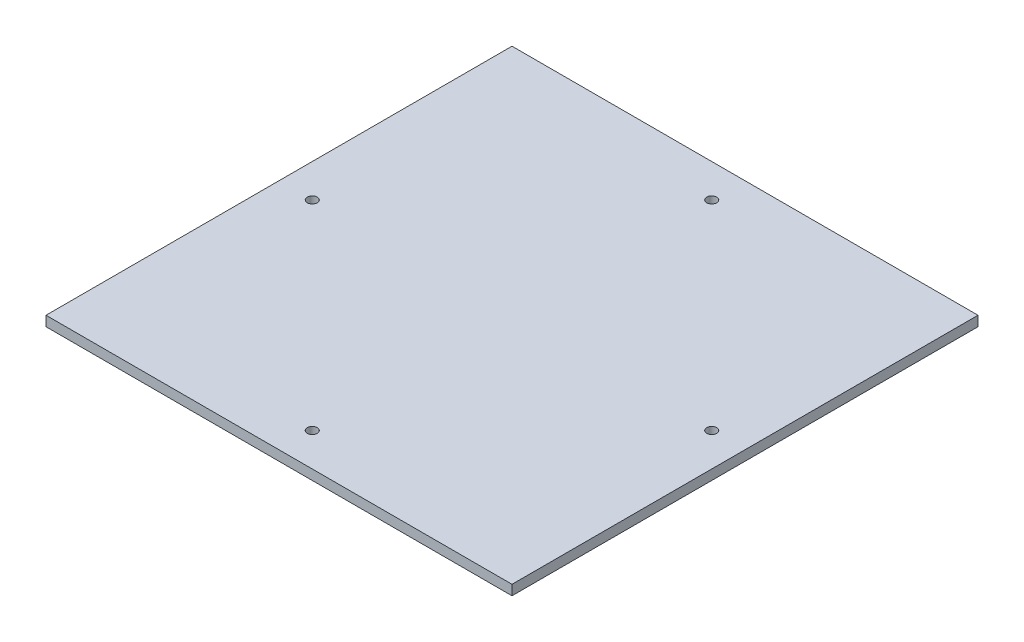
SolidWorks part; units mm, degrees
ref_plane "前视基准面" through (0, 0, 0) normal (0, 0, 1) x (1, 0, 0)
ref_plane "上视基准面" through (0, 0, 0) normal (0, 1, 0) x (1, 0, 0)
ref_plane "右视基准面" through (0, 0, 0) normal (1, 0, 0) x (0, 0, -1)
other "Configuration Table"
sketch "草图1" plane through (0, 0, 0) normal (0, 1, 0) x (1, 0, 0)
  line L1 (70, -70) -> (-70, -70)
  line L2 (70, -70) -> (70, 70)
  line L3 (70, 70) -> (-70, 70)
  line L4 (-70, -70) -> (-70, 70)
  line L5 (70, -70) -> (-70, 70) construction
  line L6 (70, 70) -> (-70, -70) construction
  point P0 (0, 0)
  dimension "D1" = 140
  dimension "D2" = 140
extrude "凸台-拉伸1" add sketch "草图1" along normal blind 3
sketch "草图2" plane through (0, 3, 0) normal (0, 1, 0) x (1, 0, 0)
  circle A0 centre (0, 60) radius 1.5
  circle A1 centre (60, 0) radius 1.5
  circle A2 centre (0, -60) radius 1.5
  circle A3 centre (-60, 0) radius 1.5
extrude "切除-拉伸1" cut sketch "草图2" against normal through all
